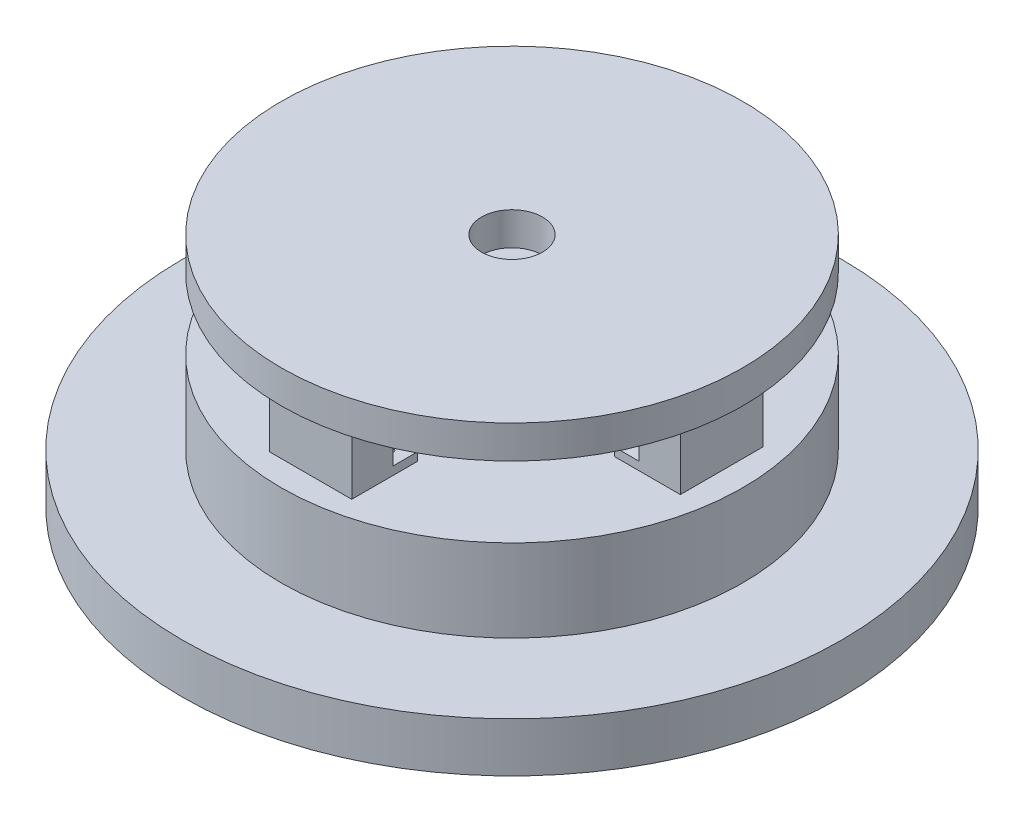
SolidWorks part; units mm, degrees
ref_plane "前视基准面" through (0, 0, 0) normal (0, 0, 1) x (1, 0, 0)
ref_plane "上视基准面" through (0, 0, 0) normal (0, 1, 0) x (1, 0, 0)
ref_plane "右视基准面" through (0, 0, 0) normal (1, 0, 0) x (0, 0, -1)
other "Configuration Table"
sketch "草图1" plane through (0, 0, 0) normal (0, 1, 0) x (1, 0, 0)
  circle A0 centre (0, 0) radius 200
  dimension "D1" = 400
extrude "凸台-拉伸1" add sketch "草图1" along normal blind 30 contours A0
sketch "草图2" plane through (0, 30, 0) normal (0, 1, 0) x (1, 0, 0)
  circle A0 centre (0, 0) radius 140
  dimension "D1" = 280
extrude "凸台-拉伸2" add sketch "草图2" along normal blind 50
sketch "草图3" plane through (0, 80, 0) normal (0, 1, 0) x (1, 0, 0)
  circle A0 centre (0, 0) radius 42.5
  dimension "D1" = 85
sketch "草图4" plane through (0, 80, 0) normal (0, 1, 0) x (1, 0, 0)
  circle A0 centre (0, -42.5) radius 1.75
  circle A1 centre (0, 0) radius 42.5 construction
  circle A2 centre (-30.052, -30.052) radius 1.75
  circle A3 centre (-42.5, 0) radius 1.75
  circle A4 centre (-30.052, 30.052) radius 1.75
  circle A5 centre (0, 42.5) radius 1.75
  circle A6 centre (30.052, 30.052) radius 1.75
  circle A7 centre (42.5, 0) radius 1.75
  circle A8 centre (30.052, -30.052) radius 1.75
  point P21 (0, 0)
  dimension "D1" = 3.5
  dimension "D2" = 8
extrude "切除-拉伸1" cut sketch "草图4" against normal blind 28
sketch "草图7" plane through (0, 80, 0) normal (0, 1, 0) x (1, 0, 0)
  line L0 (-99.6623, 22.5375) -> (-99.6623, -27.4625)
  line L1 (-22.5375, -99.6623) -> (27.4625, -99.6623)
  line L2 (-22.5375, -99.6623) -> (-22.5375, -124.6623)
  line L3 (-22.5375, -124.6623) -> (27.4625, -124.6623)
  line L4 (27.4625, -99.6623) -> (27.4625, -124.6623)
  line L5 (-22.5375, -99.6623) -> (27.4625, -124.6623) construction
  line L6 (-22.5375, -124.6623) -> (27.4625, -99.6623) construction
  line L7 (-99.6623, 22.5375) -> (-124.6623, 22.5375)
  line L8 (-124.6623, 22.5375) -> (-124.6623, -27.4625)
  line L9 (-99.6623, -27.4625) -> (-124.6623, -27.4625)
  line L10 (22.5375, 99.6623) -> (-27.4625, 99.6623)
  line L11 (22.5375, 99.6623) -> (22.5375, 124.6623)
  line L12 (22.5375, 124.6623) -> (-27.4625, 124.6623)
  line L13 (-27.4625, 99.6623) -> (-27.4625, 124.6623)
  line L14 (99.6623, -22.5375) -> (99.6623, 27.4625)
  line L15 (99.6623, -22.5375) -> (124.6623, -22.5375)
  line L16 (124.6623, -22.5375) -> (124.6623, 27.4625)
  line L17 (99.6623, 27.4625) -> (124.6623, 27.4625)
  point P0 (2.4625, -112.1623)
  point P20 (0, 0)
  dimension "D1" = 25
  dimension "D2" = 50
  dimension "D3" = 4
extrude "凸台-拉伸5" add sketch "草图7" along normal blind 43
sketch "草图8" plane through (0, 80, 0) normal (0, 1, 0) x (1, 0, 0)
  line L0 (99.6623, 27.4625) -> (99.6623, -22.5375)
  line L1 (-27.4625, 99.6623) -> (22.5375, 99.6623)
  line L2 (-27.4625, 99.6623) -> (-27.4625, 84.6623)
  line L3 (-27.4625, 84.6623) -> (22.5375, 84.6623)
  line L4 (22.5375, 99.6623) -> (22.5375, 84.6623)
  line L5 (99.6623, 27.4625) -> (84.6623, 27.4625)
  line L6 (84.6623, 27.4625) -> (84.6623, -22.5375)
  line L7 (99.6623, -22.5375) -> (84.6623, -22.5375)
  line L8 (27.4625, -99.6623) -> (-22.5375, -99.6623)
  line L9 (27.4625, -99.6623) -> (27.4625, -84.6623)
  line L10 (27.4625, -84.6623) -> (-22.5375, -84.6623)
  line L11 (-22.5375, -99.6623) -> (-22.5375, -84.6623)
  line L12 (-99.6623, -27.4625) -> (-99.6623, 22.5375)
  line L13 (-99.6623, -27.4625) -> (-84.6623, -27.4625)
  line L14 (-84.6623, -27.4625) -> (-84.6623, 22.5375)
  line L15 (-99.6623, 22.5375) -> (-84.6623, 22.5375)
  point P20 (0, 0)
  dimension "D1" = 15
  dimension "D2" = 4
extrude "凸台-拉伸6" add sketch "草图8" along normal blind 5
sketch "草图9" plane through (0, 85, 0) normal (0, 1, 0) x (1, 0, 0)
  circle A0 centre (18.6562, -92.1623) radius 1.75
  circle A1 centre (-11.971, -92.1623) radius 1.75
  circle A2 centre (-92.1623, 11.971) radius 1.75
  circle A3 centre (-92.1623, -18.6562) radius 1.75
  circle A4 centre (11.971, 92.1623) radius 1.75
  circle A5 centre (-18.6562, 92.1623) radius 1.75
  circle A6 centre (92.1623, -11.971) radius 1.75
  circle A7 centre (92.1623, 18.6562) radius 1.75
  point P19 (0, 0)
  dimension "D1" = 3.5
  dimension "D2" = 3.5
  dimension "D3" = 4
extrude "切除-拉伸2" cut sketch "草图9" against normal blind 20
sketch "草图10" plane through (0, 123, 0) normal (0, 1, 0) x (1, 0, 0)
  circle A0 centre (0, 0) radius 140
extrude "凸台-拉伸7" add sketch "草图10" along normal blind 20
sketch "草图11" plane through (0, 143, 0) normal (0, 1, 0) x (1, 0, 0)
  circle A0 centre (0, 0) radius 2.5
  dimension "D1" = 5
extrude "切除-拉伸3" cut sketch "草图11" against normal blind 20
sketch "草图13" plane through (0, 143, 0) normal (0, 1, 0) x (1, 0, 0)
  circle A0 centre (0, 0) radius 18.5
  dimension "D1" = 37
extrude "切除-拉伸4" cut sketch "草图13" against normal up to next
